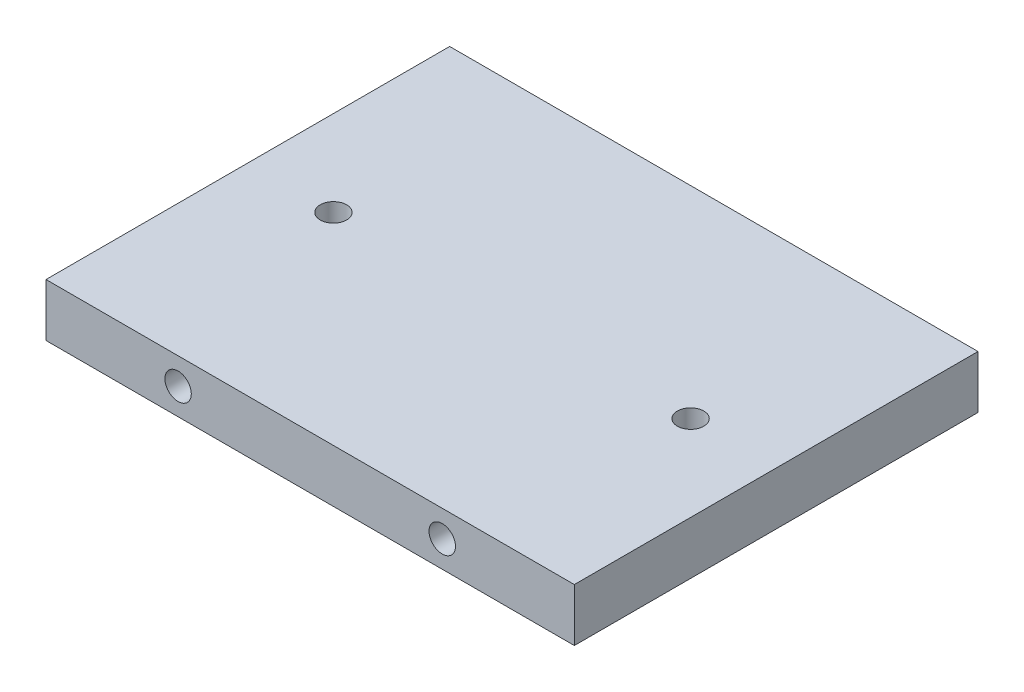
SolidWorks part; units mm, degrees
material "ABS"
ref_plane "Front Plane" through (0, 0, 0) normal (0, 0, 1) x (1, 0, 0)
ref_plane "Top Plane" through (0, 0, 0) normal (0, 1, 0) x (1, 0, 0)
ref_plane "Right Plane" through (0, 0, 0) normal (1, 0, 0) x (0, 0, -1)
sketch "Sketch1" plane through (0, 0, 0) normal (0, 1, 0) x (1, 0, 0)
  line L0 (0, 97.028) -> (63.5, 97.028)
  line L1 (63.5, 97.028) -> (63.5, 0)
  line L2 (63.5, 0) -> (-63.5, 0)
  line L3 (-63.5, 0) -> (-63.5, 97.028)
  line L4 (-63.5, 97.028) -> (0, 97.028)
  line L5 (-63.5, 48.514) -> (-42.926, 48.514) construction
  line L6 (-42.926, 48.514) -> (42.926, 48.514) construction
  line L7 (42.926, 48.514) -> (63.5, 48.514) construction
  circle A0 centre (-42.926, 48.514) radius 3.175
  circle A1 centre (42.926, 48.514) radius 3.175
  dimension "D3" = 6.35
  dimension "D1" = 127
  dimension "D2" = 48.514
  dimension "D4" = 85.852
extrude "Boss-Extrude1" add sketch "Sketch1" along normal blind 12.7
sketch "Sketch3" plane through (0, 0, 0) normal (0, 0, 1) x (1, 0, 0)
  line L0 (-78.7739, 6.35) -> (79.2116, 6.35) construction
  line L1 (-63.5, 12.7) -> (-63.5, 0) construction
  line L2 (63.5, 12.7) -> (63.5, 0) construction
  circle A0 centre (-31.75, 6.35) radius 3.175
  circle A1 centre (31.75, 6.35) radius 3.175
  point P12 (-63.5, 6.35)
  dimension "D1" = 6.35
  dimension "D2" = 31.75
  dimension "D3" = 31.75
extrude "Cut-Extrude1" cut sketch "Sketch3" against normal through all
